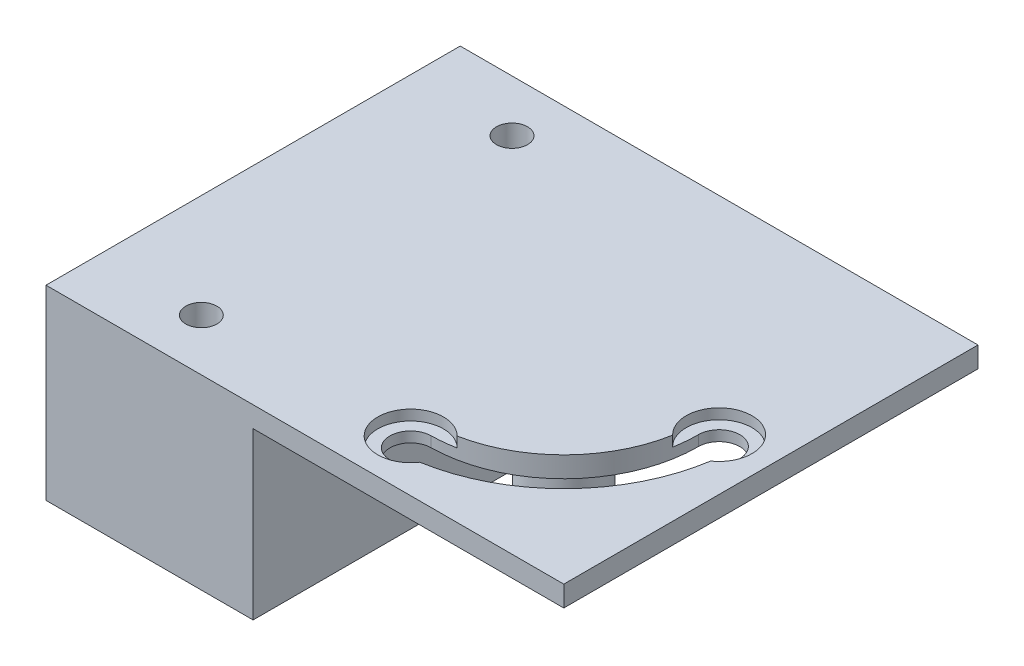
SolidWorks part; units mm, degrees
material "ABS"
ref_plane "Front Plane" through (0, 0, 0) normal (0, 0, 1) x (1, 0, 0)
ref_plane "Top Plane" through (0, 0, 0) normal (0, 1, 0) x (1, 0, 0)
ref_plane "Right Plane" through (0, 0, 0) normal (1, 0, 0) x (0, 0, -1)
sketch "Sketch1" plane through (0, 0, 0) normal (0, 1, 0) x (1, 0, 0)
  line L1 (-30, 20) -> (30, 20)
  line L2 (-30, 20) -> (-30, -20)
  line L3 (-30, -20) -> (30, -20)
  line L4 (30, 20) -> (30, -20)
  line L5 (-30, 20) -> (30, -20) construction
  line L6 (-30, -20) -> (30, 20) construction
  point P0 (0, 0)
  dimension "D1" = 40
  dimension "D2" = 60
extrude "Boss-Extrude1" add sketch "Sketch1" along normal blind 2
sketch "Sketch4" plane through (0, 2, 0) normal (0, 1, 0) x (1, 0, 0)
  line L0 (0, 20) -> (0, -20) construction
  line L1 (30, 20) -> (-30, 20) construction
  line L2 (-30, -20) -> (30, -20) construction
  arc A1 (27, 0) -> (10.2388, -16.9983) centre (10, 0) cw
  arc A7 (25, 0) -> (15.721, -13.8661) centre (10, 0) cw construction
  circle A11 centre (10, 0) radius 3.5 construction
  arc A12 (23, 0) -> (10.1826, -12.9987) centre (10, 0) cw
  arc A13 (23, 0) -> (27, 0) centre (25, 0) cw
  arc A14 (10.1826, -12.9987) -> (10.2388, -16.9983) centre (10.2107, -14.9985) ccw
  point P34 (10, 0)
  dimension "D3" = 13
  dimension "D4" = 17
  dimension "D1" = 20
  dimension "D2" = 10
extrude "Cut-Extrude1" cut sketch "Sketch4" against normal blind 14
sketch "Sketch6" plane through (0, 0, 0) normal (0, -1, 0) x (1, 0, 0)
  line L0 (0, -20) -> (-30, -20)
  line L2 (0, 20) -> (0, -20)
  line L5 (-30, 20) -> (-30, -20)
  line L6 (0, 20) -> (-30, 20)
extrude "Boss-Extrude4" add sketch "Sketch6" along normal blind 16
sketch "Sketch7" plane through (0, 2, 0) normal (0, 1, 0) x (1, 0, 0)
  line L2 (0, 20) -> (0, -20) construction
  line L4 (0, 12.9854) -> (0, -5.668) construction
  point P14 (-10, -15)
  point P17 (-10, 15)
  dimension "D1" = 10
  dimension "D2" = 10
sketch "Sketch8" plane through (0, 0, 0) normal (0, -1, 0) x (1, 0, 0)
  circle A0 centre (10, 0) radius 3.5
extrude "Boss-Extrude5" add sketch "Sketch8" along normal blind 16
sketch "Sketch9" plane through (0, 2, 0) normal (0, 1, 0) x (1, 0, 0)
  circle A0 centre (25, 0) radius 3.175
  circle A1 centre (10.2107, -14.9985) radius 3.175
  dimension "D1" = 6.35
  dimension "D2" = 6.35
extrude "Cut-Extrude2" cut sketch "Sketch9" against normal blind 1
sketch "Sketch10" plane through (0, 2, 0) normal (0, 1, 0) x (1, 0, 0)
  line L0 (-30, -20) -> (30, -20) construction
  line L1 (-30, 20) -> (-20, 20)
  line L2 (-30, 20) -> (-30, -20)
  line L3 (-30, -20) -> (-20, -20)
  line L4 (-20, 20) -> (-20, -20)
  dimension "D1" = 10
extrude "Cut-Extrude3" cut sketch "Sketch10" against normal blind 30
hole_wizard "Ø3.0mm Dowel Hole1" positions "Sketch11" profile "Sketch12" hole size "Ø3.0" standard "ANSI Metric" end condition through all
sketch "Sketch11" plane through (0, 2, 0) normal (0, 1, 0) x (1, 0, 0)
  point P0 (-10, 15)
  point P3 (-10, -15)
sketch "Sketch12" plane through (-10, 2, -15) normal (1, 0, 0) x (0, 0, 1)
  line L0 (0, 0) -> (0, 18)
  line L1 (0, 18) -> (1.5, 18)
  line L2 (1.5, 18) -> (1.5, 0)
  line L5 (1.5, 0) -> (0, 0)
  line L11 (0, -6.35) -> (0, 107.95) construction
  dimension "Thru Hole Dia." = 3
  dimension "Thru Hole Depth" = 18
